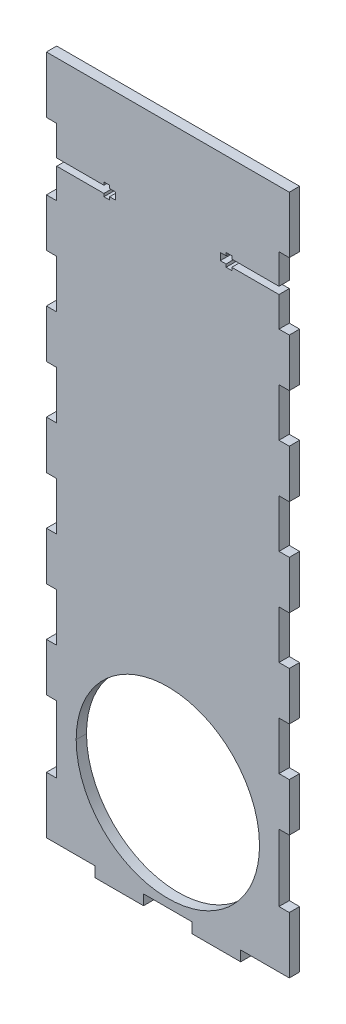
SolidWorks part; units mm, degrees
ref_plane "Front Plane" through (0, 0, 0) normal (0, 0, 1) x (1, 0, 0)
ref_plane "Top Plane" through (0, 0, 0) normal (0, 1, 0) x (1, 0, 0)
ref_plane "Right Plane" through (0, 0, 0) normal (1, 0, 0) x (0, 0, -1)
sketch "Model" plane through (0, 0, 0) normal (0, 0, 1) x (1, 0, 0)
  line L0 (1024.0257, -784.0777) -> (1024.0257, -771.0025)
  line L1 (1024.0257, -771.0025) -> (1019.5257, -771.0025)
  line L2 (1019.5257, -771.0025) -> (1019.5257, -750.0026)
  line L3 (1019.5257, -750.0026) -> (1024.0257, -750.0026)
  line L4 (1024.0257, -750.0026) -> (1024.0257, -729.0027)
  line L5 (1024.0257, -729.0027) -> (1019.5257, -729.0027)
  line L6 (1019.5257, -729.0027) -> (1019.5257, -708.0028)
  line L7 (1019.5257, -708.0028) -> (1024.0257, -708.0028)
  line L8 (1024.0257, -708.0028) -> (1024.0257, -687.0025)
  line L9 (1024.0257, -687.0025) -> (1019.5257, -687.0025)
  line L10 (1019.5257, -687.0025) -> (1019.5257, -666.0026)
  line L11 (1019.5257, -666.0026) -> (1024.0257, -666.0026)
  line L12 (1024.0257, -666.0026) -> (1024.0257, -645.0027)
  line L13 (1024.0257, -645.0027) -> (1019.5257, -645.0027)
  line L14 (1019.5257, -645.0027) -> (1019.5257, -624.0028)
  line L15 (1019.5257, -624.0028) -> (1024.0257, -624.0028)
  line L16 (1024.0257, -624.0028) -> (1024.0257, -603.0028)
  line L17 (1024.0257, -603.0028) -> (1019.5257, -603.0028)
  line L18 (1019.5257, -603.0028) -> (1019.5257, -582.0025)
  line L19 (1019.5257, -582.0025) -> (1024.0257, -582.0025)
  line L20 (1024.0257, -582.0025) -> (1024.0257, -568.9277)
  line L21 (1024.0257, -568.9277) -> (1044.6256, -568.9277)
  line L22 (1044.6256, -568.9277) -> (1044.6256, -570.1776)
  line L23 (1044.6256, -570.1776) -> (1047.1257, -570.1776)
  line L24 (1047.1257, -570.1776) -> (1047.1257, -568.9277)
  line L25 (1047.1257, -568.9277) -> (1049.6258, -568.9277)
  line L26 (1049.6258, -568.9277) -> (1049.6258, -565.8275)
  line L27 (1049.6258, -565.8275) -> (1047.1257, -565.8275)
  line L28 (1047.1257, -565.8275) -> (1047.1257, -564.5776)
  line L29 (1047.1257, -564.5776) -> (1044.6256, -564.5776)
  line L30 (1044.6256, -564.5776) -> (1044.6256, -565.8275)
  line L31 (1044.6256, -565.8275) -> (1024.0257, -565.8275)
  line L32 (1024.0257, -565.8275) -> (1024.0257, -552.7526)
  line L33 (1024.0257, -552.7526) -> (1019.5257, -552.7526)
  line L34 (1019.5257, -552.7526) -> (1019.5257, -528.0027)
  line L35 (1019.5257, -528.0027) -> (1040.7258, -528.0027)
  line L36 (1070.9758, -825.0027) -> (1061.9255, -825.0027)
  line L37 (1061.9255, -825.0027) -> (1061.9255, -829.5027)
  line L38 (1061.9255, -829.5027) -> (1040.7258, -829.5027)
  line L39 (1040.7258, -829.5027) -> (1040.7258, -825.0027)
  line L40 (1040.7258, -825.0027) -> (1019.5257, -825.0027)
  line L41 (1019.5257, -825.0027) -> (1019.5257, -800.2528)
  line L42 (1019.5257, -800.2528) -> (1024.0257, -800.2528)
  line L43 (1024.0257, -800.2528) -> (1024.0257, -787.1776)
  line L44 (1121.0258, -787.1776) -> (1121.0258, -800.2528)
  line L45 (1121.0258, -800.2528) -> (1125.5258, -800.2528)
  line L46 (1125.5258, -800.2528) -> (1125.5258, -825.0027)
  line L47 (1125.5258, -825.0027) -> (1104.3257, -825.0027)
  line L48 (1104.3257, -825.0027) -> (1104.3257, -829.5027)
  line L49 (1104.3257, -829.5027) -> (1083.126, -829.5027)
  line L50 (1083.126, -829.5027) -> (1083.126, -825.0027)
  line L51 (1083.126, -825.0027) -> (1074.0757, -825.0027)
  line L52 (1104.3257, -528.0027) -> (1125.5258, -528.0027)
  line L53 (1125.5258, -528.0027) -> (1125.5258, -552.7526)
  line L54 (1125.5258, -552.7526) -> (1121.0258, -552.7526)
  line L55 (1121.0258, -552.7526) -> (1121.0258, -565.8275)
  line L56 (1121.0258, -565.8275) -> (1100.4258, -565.8275)
  line L57 (1100.4258, -565.8275) -> (1100.4258, -564.5776)
  line L58 (1100.4258, -564.5776) -> (1097.9257, -564.5776)
  line L59 (1097.9257, -564.5776) -> (1097.9257, -565.8275)
  line L60 (1097.9257, -565.8275) -> (1095.4256, -565.8275)
  line L61 (1095.4256, -565.8275) -> (1095.4256, -568.9277)
  line L62 (1095.4256, -568.9277) -> (1097.9257, -568.9277)
  line L63 (1097.9257, -568.9277) -> (1097.9257, -570.1776)
  line L64 (1097.9257, -570.1776) -> (1100.4258, -570.1776)
  line L65 (1100.4258, -570.1776) -> (1100.4258, -568.9277)
  line L66 (1100.4258, -568.9277) -> (1121.0258, -568.9277)
  line L67 (1121.0258, -568.9277) -> (1121.0258, -582.0025)
  line L68 (1121.0258, -582.0025) -> (1125.5258, -582.0025)
  line L69 (1125.5258, -582.0025) -> (1125.5258, -603.0028)
  line L70 (1125.5258, -603.0028) -> (1121.0258, -603.0028)
  line L71 (1121.0258, -603.0028) -> (1121.0258, -624.0028)
  line L72 (1121.0258, -624.0028) -> (1125.5258, -624.0028)
  line L73 (1125.5258, -624.0028) -> (1125.5258, -645.0027)
  line L74 (1125.5258, -645.0027) -> (1121.0258, -645.0027)
  line L75 (1121.0258, -645.0027) -> (1121.0258, -666.0026)
  line L76 (1121.0258, -666.0026) -> (1125.5258, -666.0026)
  line L77 (1125.5258, -666.0026) -> (1125.5258, -687.0025)
  line L78 (1125.5258, -687.0025) -> (1121.0258, -687.0025)
  line L79 (1121.0258, -687.0025) -> (1121.0258, -708.0028)
  line L80 (1121.0258, -708.0028) -> (1125.5258, -708.0028)
  line L81 (1125.5258, -708.0028) -> (1125.5258, -729.0027)
  line L82 (1125.5258, -729.0027) -> (1121.0258, -729.0027)
  line L83 (1121.0258, -729.0027) -> (1121.0258, -750.0026)
  line L84 (1121.0258, -750.0026) -> (1125.5258, -750.0026)
  line L85 (1125.5258, -750.0026) -> (1125.5258, -771.0025)
  line L86 (1125.5258, -771.0025) -> (1121.0258, -771.0025)
  line L87 (1121.0258, -771.0025) -> (1121.0258, -784.0777)
  line L88 (1121.0258, -784.0777) -> (1121.0258, -787.1776)
  line L89 (1070.9758, -825.0027) -> (1074.0757, -825.0027)
  line L90 (1024.0257, -784.0777) -> (1024.0257, -787.1776)
  spline S2 degree 2 poles (1104.3257, -528.0027) (1090.0885, -528.0027) (1072.5257, -528.0027) knots 2 2 2 3 3 3
  spline S3 degree 2 poles (1072.5257, -528.0027) (1054.963, -528.0027) (1040.7258, -528.0027) knots 3 3 3 4 4 4
  spline S4 degree 3 poles (1032.5258, -781.4052) (1032.5258, -759.3137) (1050.4344, -741.405) (1072.5257, -741.405) (1094.6171, -741.405) (1112.5257, -759.3137) (1112.5257, -781.4052) knots 2 2 2 2 3 3 3 4 4 4 4
  spline S5 degree 3 poles (1112.5257, -781.4052) (1112.5257, -803.4967) (1094.6171, -821.4053) (1072.5257, -821.4053) (1050.4344, -821.4053) (1032.5258, -803.4967) (1032.5258, -781.4052) knots 0 0 0 0 1 1 1 2 2 2 2
  point P127 (0, 0)
extrude "Boss-Extrude1" add sketch "Model" along normal blind 4.5
